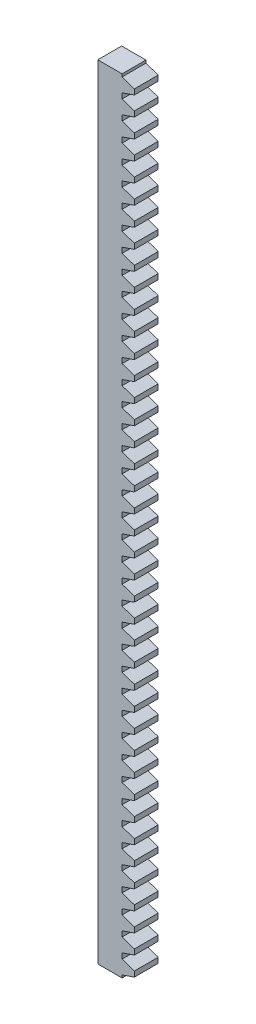
SolidWorks part; units mm, degrees
ref_plane "Plano frontal" through (0, 0, 0) normal (0, 0, 1) x (1, 0, 0)
ref_plane "Plano superior" through (0, 0, 0) normal (0, 1, 0) x (1, 0, 0)
ref_plane "Plano direito" through (0, 0, 0) normal (1, 0, 0) x (0, 0, -1)
sketch "Esboço1" plane through (0, 0, 0) normal (0, 0, 1) x (1, 0, 0)
  line L0 (-2.5965, -162.8747) -> (2.5465, -161.1158)
  line L1 (2.5465, -161.1158) -> (2.5465, -158.8842)
  line L2 (2.5465, -158.8842) -> (-2.5965, -157.1253)
  line L3 (-2.5965, -157.1253) -> (-2.5965, -154.8747)
  line L4 (-2.5965, -154.8747) -> (2.5465, -153.1158)
  line L5 (2.5465, -153.1158) -> (2.5465, -150.8842)
  line L6 (2.5465, -150.8842) -> (-2.5965, -149.1253)
  line L7 (-2.5965, -149.1253) -> (-2.5965, -146.8747)
  line L8 (-2.5965, -146.8747) -> (2.5465, -145.1158)
  line L9 (2.5465, -145.1158) -> (2.5465, -142.8842)
  line L10 (2.5465, -142.8842) -> (-2.5965, -141.1253)
  line L11 (-2.5965, -141.1253) -> (-2.5965, -138.8747)
  line L12 (-2.5965, -138.8747) -> (2.5465, -137.1158)
  line L13 (2.5465, -137.1158) -> (2.5465, -134.8842)
  line L14 (2.5465, -134.8842) -> (-2.5965, -133.1253)
  line L15 (-2.5965, -133.1253) -> (-2.5965, -130.8747)
  line L16 (-2.5965, -130.8747) -> (2.5465, -129.1158)
  line L17 (2.5465, -129.1158) -> (2.5465, -126.8842)
  line L18 (2.5465, -126.8842) -> (-2.5965, -125.1253)
  line L19 (-2.5965, -125.1253) -> (-2.5965, -122.8747)
  line L20 (-2.5965, -122.8747) -> (2.5465, -121.1158)
  line L21 (2.5465, -121.1158) -> (2.5465, -118.8842)
  line L22 (2.5465, -118.8842) -> (-2.5965, -117.1253)
  line L23 (-2.5965, -117.1253) -> (-2.5965, -114.8747)
  line L24 (-2.5965, -114.8747) -> (2.5465, -113.1158)
  line L25 (2.5465, -113.1158) -> (2.5465, -110.8842)
  line L26 (2.5465, -110.8842) -> (-2.5965, -109.1253)
  line L27 (-2.5965, -109.1253) -> (-2.5965, -106.8747)
  line L28 (-2.5965, -106.8747) -> (2.5465, -105.1158)
  line L29 (2.5465, -105.1158) -> (2.5465, -102.8842)
  line L30 (2.5465, -102.8842) -> (-2.5965, -101.1253)
  line L31 (-2.5965, -101.1253) -> (-2.5965, -98.8747)
  line L32 (-2.5965, -98.8747) -> (2.5465, -97.1158)
  line L33 (2.5465, -97.1158) -> (2.5465, -94.8842)
  line L34 (2.5465, -94.8842) -> (-2.5965, -93.1253)
  line L35 (-2.5965, -93.1253) -> (-2.5965, -90.8747)
  line L36 (-2.5965, -90.8747) -> (2.5465, -89.1158)
  line L37 (2.5465, -89.1158) -> (2.5465, -86.8842)
  line L38 (2.5465, -86.8842) -> (-2.5965, -85.1253)
  line L39 (-2.5965, -85.1253) -> (-2.5965, -82.8747)
  line L40 (-2.5965, -82.8747) -> (2.5465, -81.1158)
  line L41 (2.5465, -81.1158) -> (2.5465, -78.8842)
  line L42 (2.5465, -78.8842) -> (-2.5965, -77.1253)
  line L43 (-2.5965, -77.1253) -> (-2.5965, -74.8747)
  line L44 (-2.5965, -74.8747) -> (2.5465, -73.1158)
  line L45 (2.5465, -73.1158) -> (2.5465, -70.8842)
  line L46 (2.5465, -70.8842) -> (-2.5965, -69.1253)
  line L47 (-2.5965, -69.1253) -> (-2.5965, -66.8747)
  line L48 (-2.5965, -66.8747) -> (2.5465, -65.1158)
  line L49 (2.5465, -65.1158) -> (2.5465, -62.8842)
  line L50 (2.5465, -62.8842) -> (-2.5965, -61.1253)
  line L51 (-2.5965, -61.1253) -> (-2.5965, -58.8747)
  line L52 (-2.5965, -58.8747) -> (2.5465, -57.1158)
  line L53 (2.5465, -57.1158) -> (2.5465, -54.8842)
  line L54 (2.5465, -54.8842) -> (-2.5965, -53.1253)
  line L55 (-2.5965, -53.1253) -> (-2.5965, -50.8747)
  line L56 (-2.5965, -50.8747) -> (2.5465, -49.1158)
  line L57 (2.5465, -49.1158) -> (2.5465, -46.8842)
  line L58 (2.5465, -46.8842) -> (-2.5965, -45.1253)
  line L59 (-2.5965, -45.1253) -> (-2.5965, -42.8747)
  line L60 (-2.5965, -42.8747) -> (2.5465, -41.1158)
  line L61 (2.5465, -41.1158) -> (2.5465, -38.8842)
  line L62 (2.5465, -38.8842) -> (-2.5965, -37.1253)
  line L63 (-2.5965, -37.1253) -> (-2.5965, -34.8747)
  line L64 (-2.5965, -34.8747) -> (2.5465, -33.1158)
  line L65 (2.5465, -33.1158) -> (2.5465, -30.8842)
  line L66 (2.5465, -30.8842) -> (-2.5965, -29.1253)
  line L67 (-2.5965, -29.1253) -> (-2.5965, -26.8747)
  line L68 (-2.5965, -26.8747) -> (2.5465, -25.1158)
  line L69 (2.5465, -25.1158) -> (2.5465, -22.8842)
  line L70 (2.5465, -22.8842) -> (-2.5965, -21.1253)
  line L71 (-2.5965, -21.1253) -> (-2.5965, -18.8747)
  line L72 (-2.5965, -18.8747) -> (2.5465, -17.1158)
  line L73 (2.5465, -17.1158) -> (2.5465, -14.8842)
  line L74 (2.5465, -14.8842) -> (-2.5965, -13.1253)
  line L75 (-2.5965, -13.1253) -> (-2.5965, -10.8747)
  line L76 (-2.5965, -10.8747) -> (2.5465, -9.1158)
  line L77 (2.5465, -9.1158) -> (2.5465, -6.8842)
  line L78 (2.5465, -6.8842) -> (-2.5965, -5.1253)
  line L79 (-2.5965, -5.1253) -> (-2.5965, -2.8747)
  line L80 (-2.5965, -2.8747) -> (2.5465, -1.1158)
  line L81 (2.5465, -1.1158) -> (2.5465, 1.1158)
  line L82 (2.5465, 1.1158) -> (-2.5965, 2.8747)
  line L83 (-2.5965, 2.8747) -> (-2.5965, 5.1253)
  line L84 (-2.5965, 5.1253) -> (2.5465, 6.8842)
  line L85 (2.5465, 6.8842) -> (2.5465, 9.1158)
  line L86 (2.5465, 9.1158) -> (-2.5965, 10.8747)
  line L87 (-2.5965, 10.8747) -> (-2.5965, 13.1253)
  line L88 (-2.5965, 13.1253) -> (2.5465, 14.8842)
  line L89 (2.5465, 14.8842) -> (2.5465, 17.1158)
  line L90 (2.5465, 17.1158) -> (-2.5965, 18.8747)
  line L91 (-2.5965, 18.8747) -> (-2.5965, 21.1253)
  line L92 (-2.5965, 21.1253) -> (2.5465, 22.8842)
  line L93 (2.5465, 22.8842) -> (2.5465, 25.1158)
  line L94 (2.5465, 25.1158) -> (-2.5965, 26.8747)
  line L95 (-2.5965, 26.8747) -> (-2.5965, 29.1253)
  line L96 (-2.5965, 29.1253) -> (2.5465, 30.8842)
  line L97 (2.5465, 30.8842) -> (2.5465, 33.1158)
  line L98 (2.5465, 33.1158) -> (-2.5965, 34.8747)
  line L99 (-2.5965, 34.8747) -> (-2.5965, 37.1253)
  line L100 (-2.5965, 37.1253) -> (2.5465, 38.8842)
  line L101 (2.5465, 38.8842) -> (2.5465, 41.1158)
  line L102 (2.5465, 41.1158) -> (-2.5965, 42.8747)
  line L103 (-2.5965, 42.8747) -> (-2.5965, 45.1253)
  line L104 (-2.5965, 45.1253) -> (2.5465, 46.8842)
  line L105 (2.5465, 46.8842) -> (2.5465, 49.1158)
  line L106 (2.5465, 49.1158) -> (-2.5965, 50.8747)
  line L107 (-2.5965, 50.8747) -> (-2.5965, 53.1253)
  line L108 (-2.5965, 53.1253) -> (2.5465, 54.8842)
  line L109 (2.5465, 54.8842) -> (2.5465, 57.1158)
  line L110 (2.5465, 57.1158) -> (-2.5965, 58.8747)
  line L111 (-2.5965, 58.8747) -> (-2.5965, 61.1253)
  line L112 (-2.5965, 61.1253) -> (2.5465, 62.8842)
  line L113 (2.5465, 62.8842) -> (2.5465, 65.1158)
  line L114 (2.5465, 65.1158) -> (-2.5965, 66.8747)
  line L115 (-2.5965, 66.8747) -> (-2.5965, 69.1253)
  line L116 (-2.5965, 69.1253) -> (2.5465, 70.8842)
  line L117 (2.5465, 70.8842) -> (2.5465, 73.1158)
  line L118 (2.5465, 73.1158) -> (-2.5965, 74.8747)
  line L119 (-2.5965, 74.8747) -> (-2.5965, 77.1253)
  line L120 (-2.5965, 77.1253) -> (2.5465, 78.8842)
  line L121 (2.5465, 78.8842) -> (2.5465, 81.1158)
  line L122 (2.5465, 81.1158) -> (-2.5965, 82.8747)
  line L123 (-2.5965, 82.8747) -> (-2.5965, 85.1253)
  line L124 (-2.5965, 85.1253) -> (2.5465, 86.8842)
  line L125 (2.5465, 86.8842) -> (2.5465, 89.1158)
  line L126 (2.5465, 89.1158) -> (-2.5965, 90.8747)
  line L127 (-2.5965, 90.8747) -> (-2.5965, 93.1253)
  line L128 (-2.5965, 93.1253) -> (2.5465, 94.8842)
  line L129 (2.5465, 94.8842) -> (2.5465, 97.1158)
  line L130 (2.5465, 97.1158) -> (-2.5965, 98.8747)
  line L131 (-2.5965, 98.8747) -> (-2.5965, 101.1253)
  line L132 (-2.5965, 101.1253) -> (2.5465, 102.8842)
  line L133 (2.5465, 102.8842) -> (2.5465, 105.1158)
  line L134 (2.5465, 105.1158) -> (-2.5965, 106.8747)
  line L135 (-2.5965, 106.8747) -> (-2.5965, 109.1253)
  line L136 (-2.5965, 109.1253) -> (2.5465, 110.8842)
  line L137 (2.5465, 110.8842) -> (2.5465, 113.1158)
  line L138 (2.5465, 113.1158) -> (-2.5965, 114.8747)
  line L139 (-2.5965, 114.8747) -> (-2.5965, 117.1253)
  line L140 (-2.5965, 117.1253) -> (2.5465, 118.8842)
  line L141 (2.5465, 118.8842) -> (2.5465, 121.1158)
  line L142 (2.5465, 121.1158) -> (-2.5965, 122.8747)
  line L143 (-2.5965, 122.8747) -> (-2.5965, 125.1253)
  line L144 (-2.5965, 125.1253) -> (2.5465, 126.8842)
  line L145 (2.5465, 126.8842) -> (2.5465, 129.1158)
  line L146 (2.5465, 129.1158) -> (-2.5965, 130.8747)
  line L147 (-2.5965, 130.8747) -> (-2.5965, 133.1253)
  line L148 (-2.5965, 133.1253) -> (2.5465, 134.8842)
  line L149 (2.5465, 134.8842) -> (2.5465, 137.1158)
  line L150 (2.5465, 137.1158) -> (-2.5965, 138.8747)
  line L151 (-2.5965, 138.8747) -> (-2.5965, 141.1253)
  line L152 (-2.5965, 141.1253) -> (2.5465, 142.8842)
  line L153 (2.5465, 142.8842) -> (2.5465, 145.1158)
  line L154 (2.5465, 145.1158) -> (-2.5965, 146.8747)
  line L155 (-2.5965, 146.8747) -> (-2.5965, 149.1253)
  line L156 (-2.5965, 149.1253) -> (2.5465, 150.8842)
  line L157 (2.5465, 150.8842) -> (2.5465, 153.1158)
  line L158 (2.5465, 153.1158) -> (-2.5965, 154.8747)
  line L159 (-2.5965, 154.8747) -> (-2.5965, 157.1253)
  line L160 (-2.5965, 157.1253) -> (2.5465, 158.8842)
  line L161 (2.5465, 158.8842) -> (2.5465, 161.1158)
  line L162 (2.5465, 161.1158) -> (-2.5965, 162.8747)
  line L163 (-2.5965, 162.8747) -> (-2.5965, 164)
  line L164 (-2.5965, 164) -> (-12.7824, 164)
  line L165 (-12.7824, 164) -> (-12.7824, -164)
  line L166 (-12.7824, -164) -> (-2.5965, -164)
  line L167 (-2.5965, -164) -> (-2.5965, -162.8747)
extrude "Ressalto-extrusão1" add sketch "Esboço1" along normal mid plane 10
scale "Scale2" scale about centroid uniform scaling yes scale factor 0.487805
